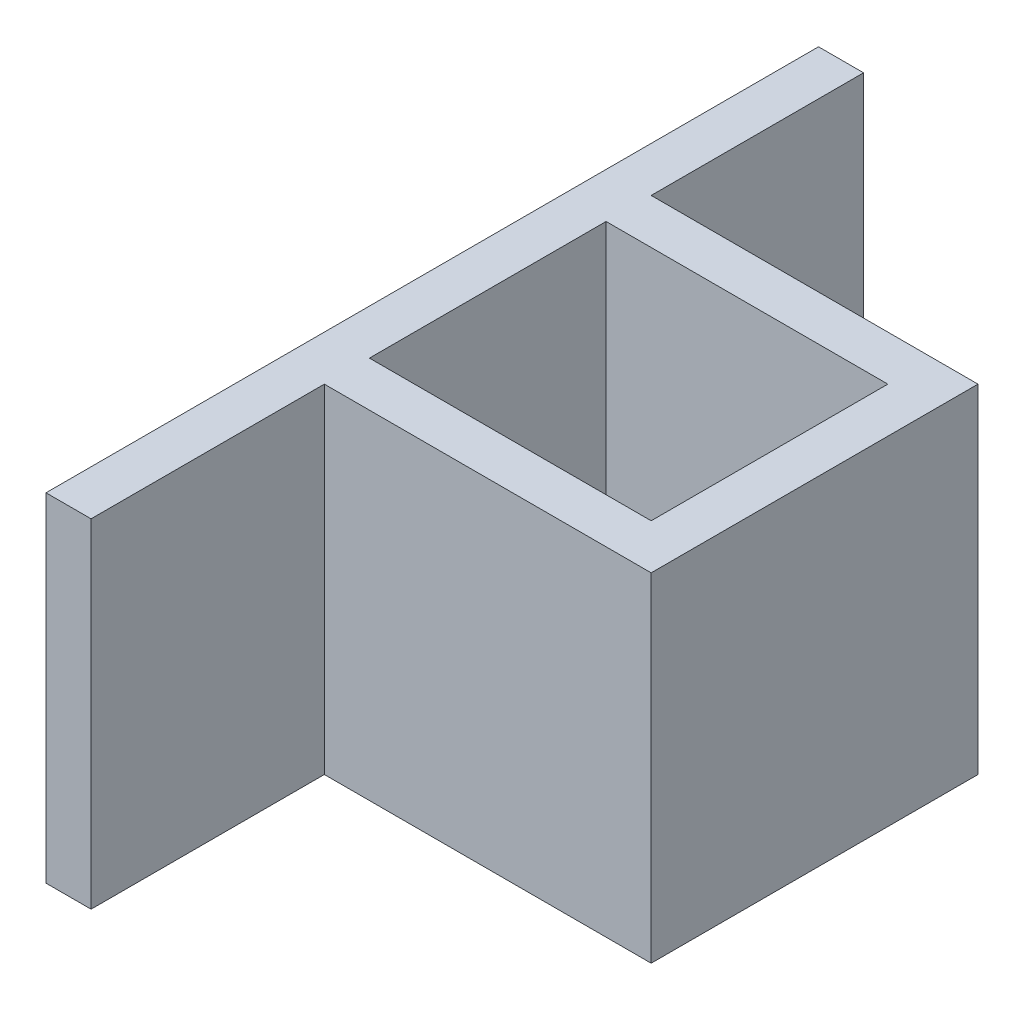
SolidWorks part; units mm, degrees
ref_plane "Front Plane" through (0, 0, 0) normal (0, 0, 1) x (1, 0, 0)
ref_plane "Top Plane" through (0, 0, 0) normal (0, 1, 0) x (1, 0, 0)
ref_plane "Right Plane" through (0, 0, 0) normal (1, 0, 0) x (0, 0, -1)
sketch "Sketch1" plane through (0, 0, 0) normal (0, 1, 0) x (1, 0, 0)
  line L0 (-2, 2) -> (-2, -12.5)
  line L1 (0, 0) -> (12.5, 0)
  line L2 (0, 0) -> (0, -10.5)
  line L3 (0, -10.5) -> (12.5, -10.5)
  line L4 (12.5, 0) -> (12.5, -10.5)
  line L5 (0, -12.5) -> (14.5, -12.5)
  line L6 (14.5, 2) -> (14.5, -12.5)
  line L7 (0, 2) -> (14.5, 2)
  line L8 (-2, 2) -> (-2, 11.424)
  line L9 (-2, 11.424) -> (0, 11.424)
  line L10 (0, 11.424) -> (0, 2)
  line L11 (-2, -12.5) -> (-2, -22.849)
  line L12 (-2, -22.849) -> (0, -22.849)
  line L13 (0, -22.849) -> (0, -12.5)
  line L14 (-2, 2) -> (14.5, 2) construction
  line L15 (-2, -12.5) -> (14.5, -12.5) construction
  dimension "D1" = 12.5
  dimension "D2" = 10.5
  dimension "D3" = 2
extrude "Boss-Extrude1" add sketch "Sketch1" along normal blind 15
